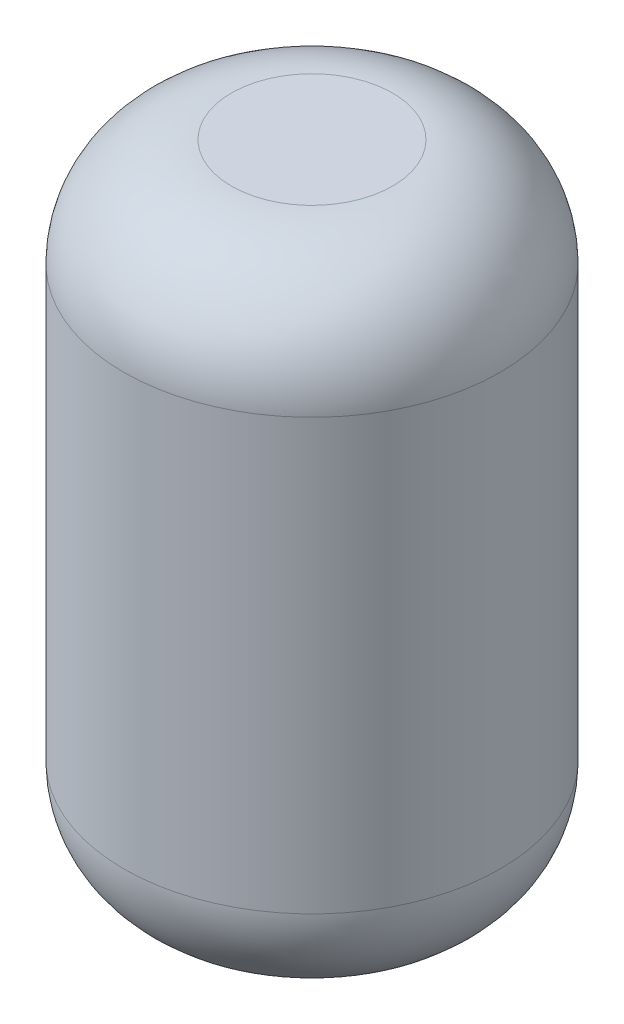
SolidWorks part; units mm, degrees
material "Custom Plastic"
ref_plane "Front Plane" through (0, 0, 0) normal (0, 0, 1) x (1, 0, 0)
ref_plane "Top Plane" through (0, 0, 0) normal (0, 1, 0) x (1, 0, 0)
ref_plane "Right Plane" through (0, 0, 0) normal (1, 0, 0) x (0, 0, -1)
sketch "Sketch1" plane through (0, 0, 0) normal (0, 1, 0) x (1, 0, 0)
  circle A0 centre (0, 0) radius 44.45
  dimension "D1" = 88.9
extrude "Boss-Extrude1" add sketch "Sketch1" along normal blind 152.4
fillet "Fillet1" radius 25.4 2 edges at (0, 0, 44.45) (0, 152.4, 44.45)
